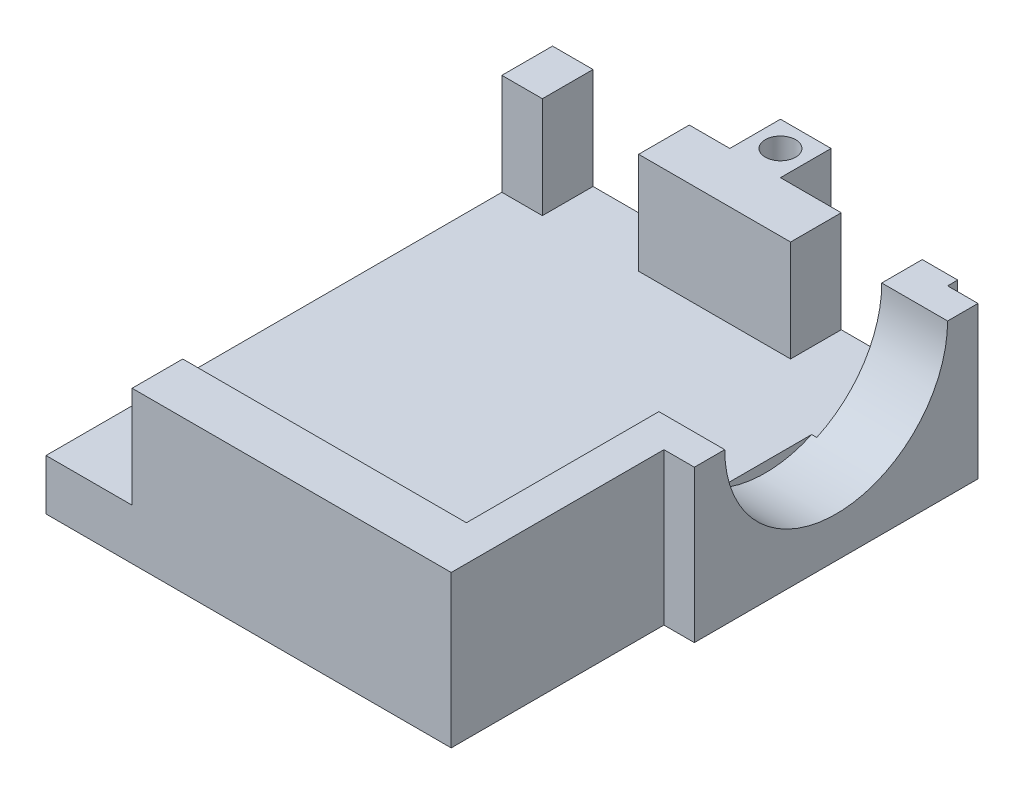
SolidWorks part; units mm, degrees
ref_plane "Front Plane" through (0, 0, 0) normal (0, 0, 1) x (1, 0, 0)
ref_plane "Top Plane" through (0, 0, 0) normal (0, 1, 0) x (1, 0, 0)
ref_plane "Right Plane" through (0, 0, 0) normal (1, 0, 0) x (0, 0, -1)
sketch "Sketch1" plane through (0, 0, 0) normal (0, 1, 0) x (1, 0, 0)
  line L1 (-20, 25) -> (20, 25)
  line L2 (-20, 25) -> (-20, -25)
  line L3 (-20, -25) -> (20, -25)
  line L4 (20, 25) -> (20, -25)
  point P5 (-20, 0)
  point P6 (0, 25)
  dimension "D1" = 40
  dimension "D2" = 50
extrude "Boss-Extrude1" add sketch "Sketch1" along normal blind 5
sketch "Sketch4" plane through (0, 5, 0) normal (0, 1, 0) x (1, 0, 0)
  line L0 (-20, -25) -> (20, -25) construction
  line L1 (20, 25) -> (16.5, 25)
  line L2 (20, 25) -> (20, -25)
  line L4 (16.5, 25) -> (16.5, -20)
  line L5 (20, 25) -> (-20, 25) construction
  line L8 (16.5, -20) -> (-6.5, -20)
  line L9 (-6.5, -25) -> (-6.5, -20)
  line L10 (-20, 25) -> (-16, 25)
  line L11 (-20, 25) -> (-20, 20)
  line L12 (-20, 20) -> (-16, 20)
  line L13 (-16, 25) -> (-16, 20)
  line L14 (-6.5, 25) -> (8.5, 25)
  line L15 (-6.5, 25) -> (-6.5, 20)
  line L16 (-6.5, 20) -> (8.5, 20)
  line L17 (8.5, 25) -> (8.5, 20)
  line L18 (-6.5, -25) -> (20, -25)
  line L19 (-11.5, 25) -> (-11.5, 20) construction
  line L20 (-11.5, 20) -> (-6.5, 20) construction
  line L21 (-16, -25) -> (-16, -20) construction
  line L22 (-16, -20) -> (-20, -20) construction
  line L23 (-20, 25) -> (-20, -25) construction
  line L25 (-6.5, -20) -> (-11.5, -20)
  line L26 (-6.5, -20) -> (-6.5, -25)
  line L27 (-6.5, -25) -> (-11.5, -25)
  line L28 (-11.5, -20) -> (-11.5, -25)
  line M20 (-20, -25) -> (20, -25)
  line M21 (20, -25) -> (20, 25)
  line M22 (20, 25) -> (-20, 25)
  dimension "D1" = 3.5
  dimension "D2" = 5
  dimension "D3" = 4
  dimension "D4" = 15
  dimension "D5" = 5
  dimension "D6" = 8
extrude "Boss-Extrude5" add sketch "Sketch4" along normal blind 10 contours L9 L4 L8 M20 M21 M22 | L17 L15 L16 M22 | L11 L10 L13 L12 | L26 L25 L28 L27
sketch "Sketch7" plane through (20, 0, 0) normal (1, 0, 0) x (0, 0, -1)
  line L0 (-25, 15) -> (25, 15) construction
  line L1 (-1, 15) -> (21, 15)
  line L2 (25, 15) -> (25, 0) construction
  arc A0 (-1, 15) -> (21, 15) centre (10, 15) ccw
  dimension "D1" = 22
  dimension "D2" = 15
extrude "Cut-Extrude2" cut sketch "Sketch7" against normal blind 4
sketch "Sketch8" plane through (20, 0, 0) normal (1, 0, 0) x (0, 0, -1)
  line L0 (-1, 15) -> (-4, 15)
  line L1 (-25, 15) -> (-1, 15) construction
  line L2 (-4, 15) -> (-4, 0)
  line L3 (-25, 0) -> (25, 0) construction
  line L4 (-4, 0) -> (24, 0)
  line L5 (24, 0) -> (24, 15)
  line L6 (21, 15) -> (25, 15) construction
  line L7 (24, 15) -> (21, 15)
  line L8 (25, 15) -> (25, 0) construction
  arc A0 (-1, 15) -> (21, 15) centre (10, 15) ccw
  dimension "D2" = 22
  dimension "D1" = 3
  dimension "D3" = 1
extrude "Boss-Extrude7" add sketch "Sketch8" along normal blind 3
sketch "Sketch9" plane through (0, 0, -25) normal (0, 0, -1) x (-1, 0, 0)
  line L0 (-8.5, 15) -> (6.5, 15) construction
  line L1 (2.5, 10) -> (-2.5, 10)
  line L2 (2.5, 10) -> (2.5, 15)
  line L3 (2.5, 15) -> (-2.5, 15)
  line L4 (-2.5, 10) -> (-2.5, 15)
  point P6 (0, 10)
  dimension "D1" = 5
  dimension "D2" = 5
extrude "Boss-Extrude8" add sketch "Sketch9" along normal blind 5
sketch "Sketch10" plane through (0, 10, 0) normal (0, -1, 0) x (1, 0, 0)
  line L0 (2.5, -25) -> (-2.5, -25) construction
  line L1 (2.5, -30) -> (2.5, -25) construction
  circle A0 centre (0, -27.5) radius 1.5
  point P4 (0, -25)
  point P7 (2.5, -27.5)
  dimension "D1" = 3
extrude "Cut-Extrude3" cut sketch "Sketch10" against normal blind 5
